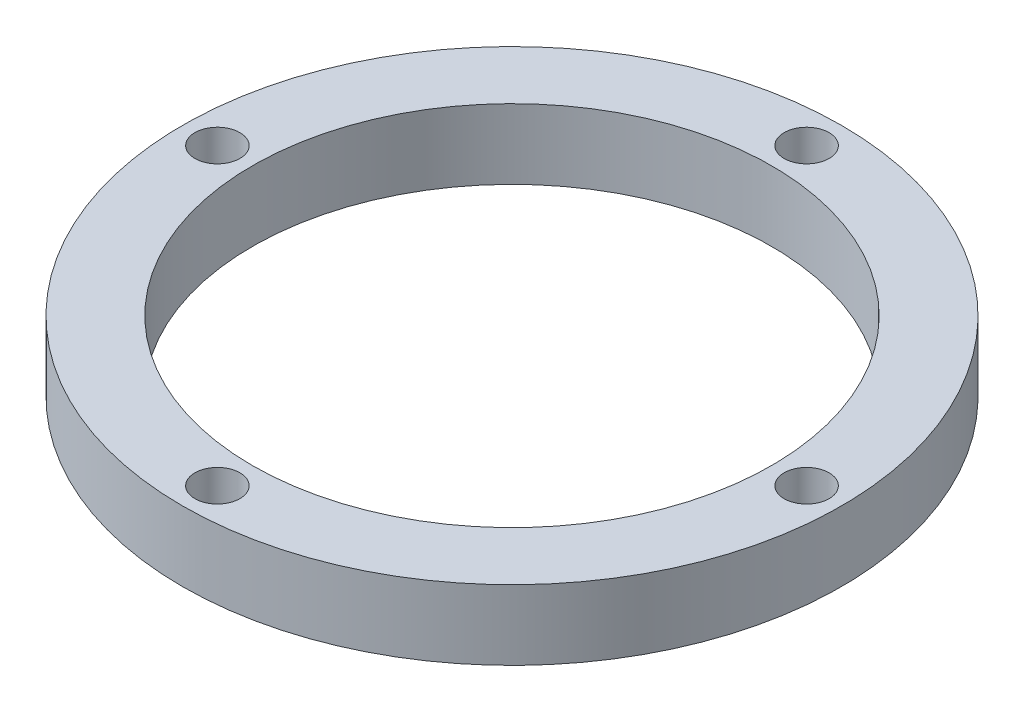
SolidWorks part; units mm, degrees
ref_plane "Front Plane" through (0, 0, 0) normal (0, 0, 1) x (1, 0, 0)
ref_plane "Top Plane" through (0, 0, 0) normal (0, 1, 0) x (1, 0, 0)
ref_plane "Right Plane" through (0, 0, 0) normal (1, 0, 0) x (0, 0, -1)
sketch "Sketch1" plane through (0, 0, 0) normal (0, 1, 0) x (1, 0, 0)
  circle A0 centre (0, 0) radius 26
  circle A1 centre (0, 0) radius 33
  dimension "D1" = 52
  dimension "D2" = 7
extrude "Boss-Extrude1" add sketch "Sketch1" along normal blind 7
sketch "Sketch5" plane through (0, 7, 0) normal (0, 1, 0) x (1, 0, 0)
  circle A0 centre (29.5, 0) radius 2.25
  circle A1 centre (0, 0) radius 26 construction
  dimension "D1" = 4.5
  dimension "D2" = 29.5
extrude "Cut-Extrude1" cut sketch "Sketch5" against normal through all
sketch "Sketch7" plane through (0, 0, 0) normal (0, 0, 1) x (1, 0, 0)
  line L0 (0, 0) -> (0, 5.0232) construction
pattern_circular "CirPattern1" count 4 over 360 about axis through (0, 0, 0) along (0, 1, 0) of "Cut-Extrude1"
